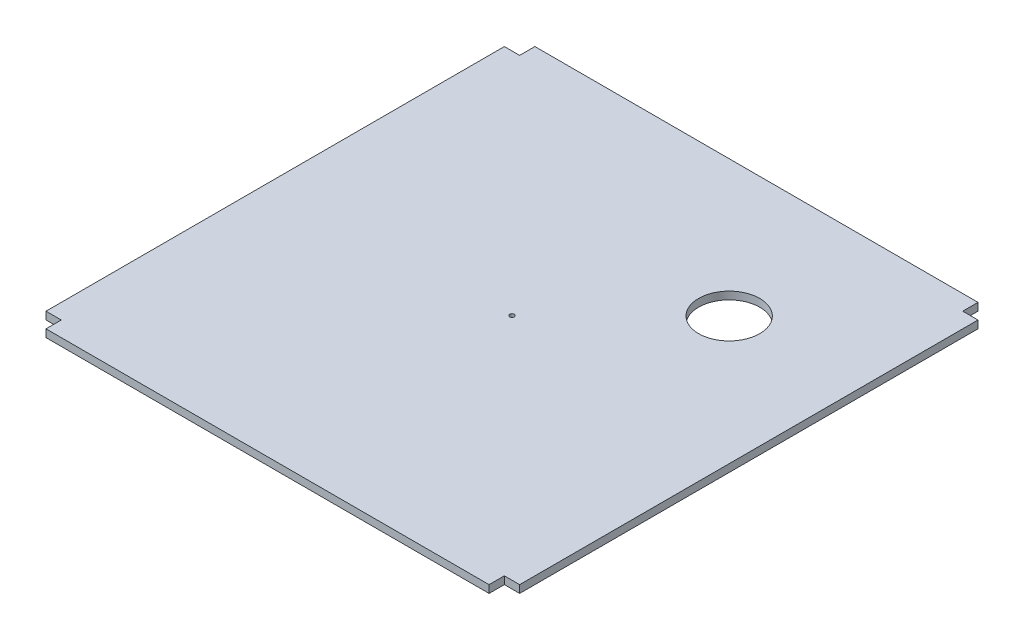
SolidWorks part; units mm, degrees
ref_plane "前视基准面" through (0, 0, 0) normal (0, 0, 1) x (1, 0, 0)
ref_plane "上视基准面" through (0, 0, 0) normal (0, 1, 0) x (1, 0, 0)
ref_plane "右视基准面" through (0, 0, 0) normal (1, 0, 0) x (0, 0, -1)
other "Configuration Table"
sketch "草图1" plane through (0, 0, 0) normal (0, 1, 0) x (1, 0, 0)
  line L0 (-155, 160) -> (155, 160)
  line L1 (-155, -160) -> (155, -160)
  line L4 (155, -160) -> (155, 160)
  line L5 (-155, -160) -> (155, 160) construction
  line L6 (-155, 160) -> (155, -160) construction
  line L18 (-155, 160) -> (-155, -160)
  point P0 (0, 0)
  dimension "D1" = 320
extrude "凸台-拉伸1" add sketch "草图1" along normal blind 5
sketch "草图4" plane through (0, 5, 0) normal (0, 1, 0) x (1, 0, 0)
  line L0 (0, 0) -> (0, -16.5407) construction
  line L1 (-155, 160) -> (-145, 160)
  line L2 (-155, 160) -> (-155, 150)
  line L3 (-155, 150) -> (-145, 150)
  line L4 (-145, 160) -> (-145, 150)
  line L5 (0, 0) -> (15.9713, 0) construction
  line L6 (-145, -160) -> (-145, -150)
  line L7 (-155, -150) -> (-145, -150)
  line L8 (-155, -160) -> (-155, -150)
  line L9 (-155, -160) -> (-145, -160)
  line L10 (155, -160) -> (145, -160)
  line L11 (155, -160) -> (155, -150)
  line L12 (155, -150) -> (145, -150)
  line L13 (145, -160) -> (145, -150)
  line L14 (145, 160) -> (145, 150)
  line L15 (155, 150) -> (145, 150)
  line L16 (155, 160) -> (155, 150)
  line L17 (155, 160) -> (145, 160)
  circle A0 centre (0, 0) radius 1.5
  circle A3 centre (71.3156, 70.8266) radius 20 construction
  circle A4 centre (71.3156, 70.8266) radius 20
  dimension "D1" = 10
extrude "切除-拉伸2" cut sketch "草图4" against normal blind 5
